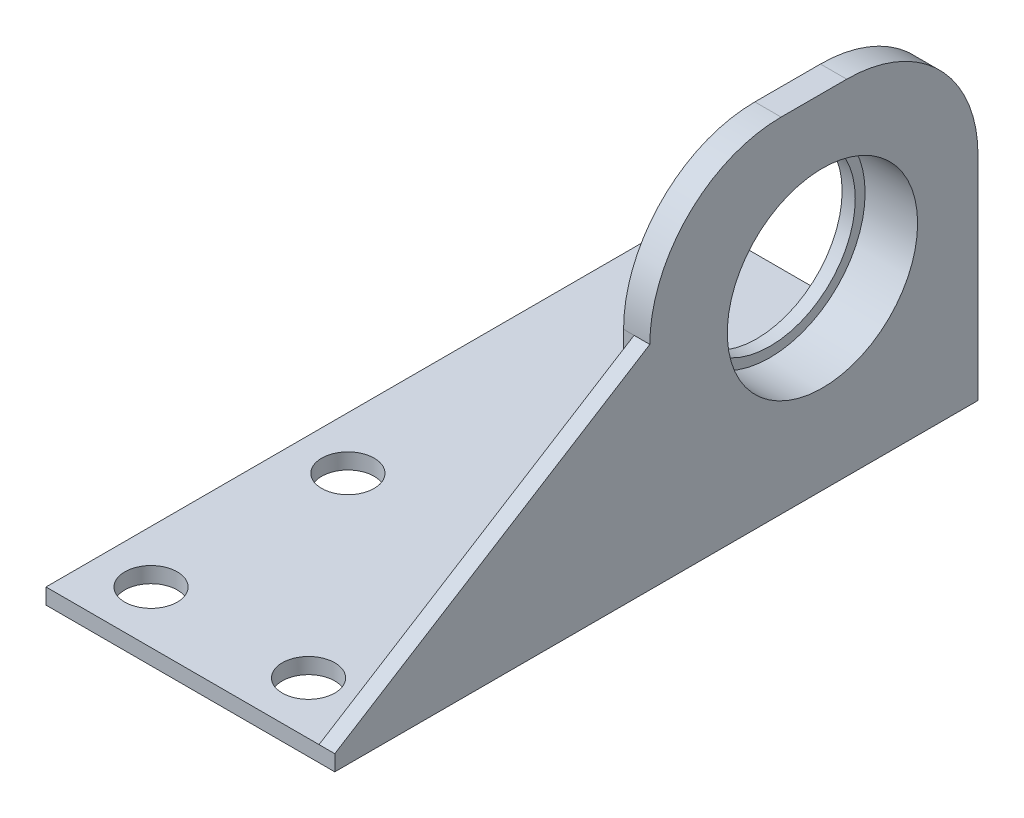
SolidWorks part; units mm, degrees
ref_plane "前视基准面" through (0, 0, 0) normal (0, 0, 1) x (1, 0, 0)
ref_plane "上视基准面" through (0, 0, 0) normal (0, 1, 0) x (1, 0, 0)
ref_plane "右视基准面" through (0, 0, 0) normal (1, 0, 0) x (0, 0, -1)
sketch "草图1" plane through (0, 0, 0) normal (1, 0, 0) x (0, 0, -1)
  line L2 (0, 0) -> (49, 0)
  line L3 (24.5, 0) -> (24.5, -2.9169) construction
  line L6 (0, 0) -> (0, 1.2)
  line L7 (0, 1.2) -> (49, 1.2)
  line L8 (49, 0) -> (49, 1.2)
  point P0 (0, -0.3842)
  point P14 (24.5, 1.2)
  dimension "D1" = 1.2
  dimension "D2" = 49
extrude "凸台-拉伸1" add sketch "草图1" along normal blind 22
sketch "草图2" plane through (0, 1.2, 0) normal (0, 1, 0) x (1, 0, 0)
  line L0 (10, 38.352) -> (10, 0) construction
  line L3 (35.9149, 19) -> (-5.3494, 19) construction
  line L6 (0, 11.5) -> (49.6699, 11.5) construction
  line L8 (22, 0) -> (0, 0) construction
  line L9 (0, 49) -> (0, 0) construction
  circle A0 centre (16, 19) radius 2
  circle A1 centre (4, 19) radius 2
  circle A2 centre (4, 4) radius 2
  circle A3 centre (16, 4) radius 2
  point P2 (20, 38.352)
  point P3 (0, 0)
  point P4 (20, 0)
  point P8 (43.4149, 48)
  point P9 (2.1506, 28.3075)
  point P10 (0, 0)
  point P18 (0, 13.7305)
  point P19 (0, 0)
  point P24 (7.5, 48)
  point P25 (0, 0)
  point P26 (0, 0)
  point P27 (0, 0)
  point P28 (0, 20)
  dimension "D1" = 12
  dimension "D2" = 4
  dimension "D3" = 15
  dimension "D4" = 4
  dimension "D5" = 10
extrude "切除-拉伸1" cut sketch "草图2" against normal up to next
sketch "草图3" plane through (0, 1.2, 0) normal (0, 1, 0) x (1, 0, 0)
  line L0 (22, 49) -> (0, 49) construction
  line L1 (20, 49) -> (22, 49)
  line L2 (20, 49) -> (20, 24)
  line L3 (20, 24) -> (22, 24)
  line L4 (22, 49) -> (22, 24)
  line L6 (22, 49) -> (22, 0) construction
  dimension "D1" = 2
  dimension "D2" = 25
extrude "凸台-拉伸2" add sketch "草图3" along normal blind 25
sketch "草图4" plane through (22, 0, 0) normal (1, 0, 0) x (0, 0, -1)
  line L1 (49, 26.2) -> (49, 0) construction
  line L2 (0, 0) -> (49, 0) construction
  circle A0 centre (37.15, 14) radius 7.25
  point P2 (28.15, 17.7395)
  dimension "D1" = 14.5
  dimension "D2" = 14
  dimension "D3" = 11.85
extrude "切除-拉伸2" cut sketch "草图4" against normal up to next
sketch "草图5" plane through (20, 0, 0) normal (-1, 0, 0) x (0, 0, 1)
  circle A0 centre (-37.15, 14) radius 8
  circle A1 centre (-37.15, 14) radius 7.25
  circle A2 centre (-37.15, 14) radius 7.25 construction
  dimension "D2" = 16
extrude "凸台-拉伸3" add sketch "草图5" along normal blind 3
sketch "草图6" plane through (17, 0, 0) normal (-1, 0, 0) x (0, 0, 1)
  circle A0 centre (-37.15, 14) radius 8
  circle A1 centre (-37.15, 14) radius 6.5
  circle A2 centre (-37.15, 14) radius 8 construction
  dimension "D1" = 13
extrude "凸台-拉伸4" add sketch "草图6" against normal blind 1
sketch "草图7" plane through (17, 0, 0) normal (-1, 0, 0) x (0, 0, 1)
  line L0 (-37.15, 14) -> (-37.15, -2.2758) construction
  line L1 (-38.15, 7.5) -> (-36.15, 7.5)
  line L2 (-36.15, 7.5) -> (-36.15, 1.2)
  line L3 (-49, 1.2) -> (0, 1.2) construction
  line L4 (-36.15, 1.2) -> (-38.15, 1.2)
  line L5 (-49, 1.2) -> (-24, 1.2) construction
  line L6 (-38.15, 7.5) -> (-38.15, 1.2)
  circle A0 centre (-37.15, 14) radius 6.5 construction
  point P12 (-37.15, 1.2)
  point P13 (-37.15, 7.5)
  dimension "D1" = 1
extrude "凸台-拉伸5" add sketch "草图7" against normal up to next
fillet "圆角1" radius 10 2 edges at (21, 26.2, -49) (21, 26.2, -24)
sketch "草图8" plane through (22, 0, 0) normal (1, 0, 0) x (0, 0, -1)
  line L0 (0, 1.2) -> (24, 16.2)
  line L1 (24, 16.2) -> (24, 1.2)
  line L2 (24, 1.2) -> (0, 1.2)
extrude "凸台-拉伸6" add sketch "草图8" against normal blind 1.2
